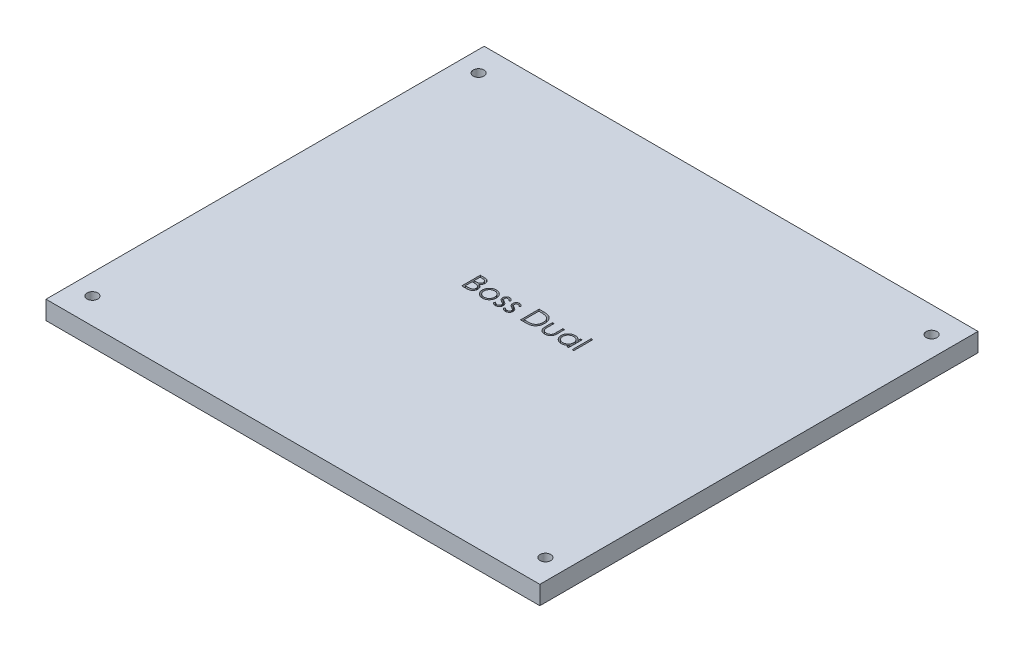
SolidWorks part; units mm, degrees
ref_plane "Front Plane" through (0, 0, 0) normal (0, 0, 1) x (1, 0, 0)
ref_plane "Top Plane" through (0, 0, 0) normal (0, 1, 0) x (1, 0, 0)
ref_plane "Right Plane" through (0, 0, 0) normal (1, 0, 0) x (0, 0, -1)
sketch "Sketch2" plane through (0, 0, 0) normal (0, 1, 0) x (1, 0, 0)
  line L1 (-84.455, -74.93) -> (84.455, -74.93)
  line L2 (-84.455, -74.93) -> (-84.455, 74.93)
  line L3 (-84.455, 74.93) -> (84.455, 74.93)
  line L4 (84.455, -74.93) -> (84.455, 74.93)
  line L5 (-84.455, -74.93) -> (84.455, 74.93) construction
  line L6 (-84.455, 74.93) -> (84.455, -74.93) construction
  point P0 (0, 0)
  dimension "D1" = 149.86
  dimension "D2" = 168.91
extrude "Boss-Extrude1" add sketch "Sketch2" along normal blind 6.35
sketch "Sketch3" plane through (0, 6.35, 0) normal (0, 1, 0) x (1, 0, 0)
  line L1 (-77.47, -66.04) -> (77.47, -66.04)
  line L2 (-77.47, -66.04) -> (-77.47, 66.04)
  line L3 (-77.47, 66.04) -> (77.47, 66.04)
  line L4 (77.47, -66.04) -> (77.47, 66.04)
  line L5 (-77.47, -66.04) -> (77.47, 66.04) construction
  line L6 (-77.47, 66.04) -> (77.47, -66.04) construction
  circle A0 centre (-77.47, 66.04) radius 1.8288
  circle A1 centre (77.47, 66.04) radius 1.8288
  circle A2 centre (77.47, -66.04) radius 1.8288
  circle A3 centre (-77.47, -66.04) radius 1.8288
  point P0 (0, 0)
  dimension "D3" = 3.6576
  dimension "D1" = 132.08
  dimension "D2" = 154.94
  dimension "D4" = 2
  dimension "D5" = 2
extrude "Cut-Extrude1" cut sketch "Sketch3" against normal through all contours A3 | A2 | A1 | A0
sketch "Sketch5" plane through (0, 6.35, 0) normal (0, 1, 0) x (1, 0, 0)
  text T0 "Boss Dual" font "Century Gothic" height 6.35
extrude "Cut-Extrude2" cut sketch "Sketch5" against normal blind 2.54
